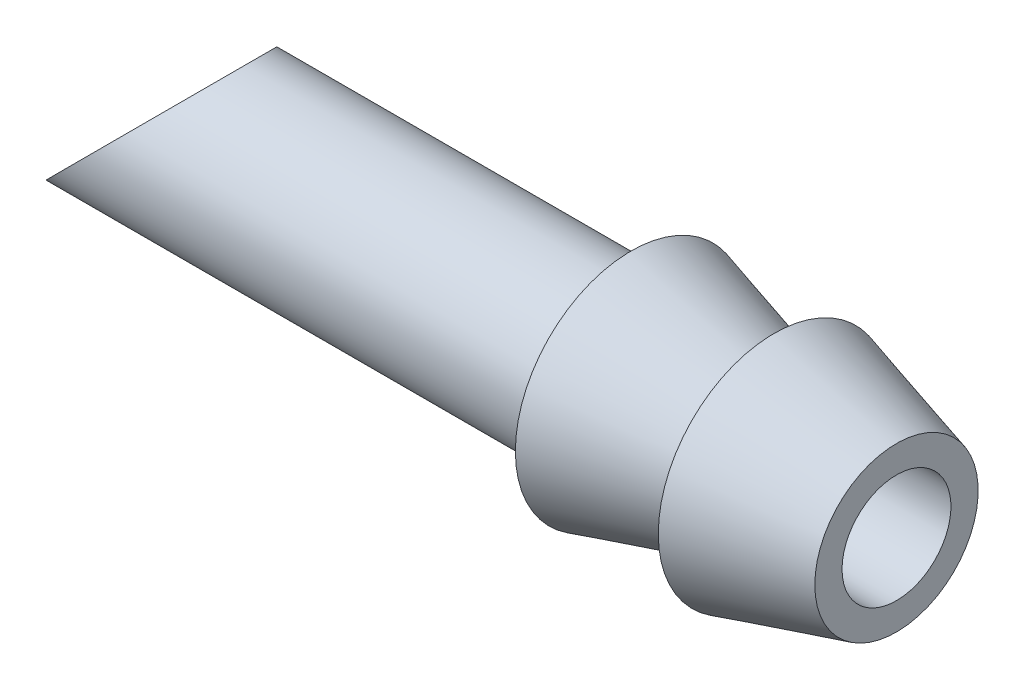
SolidWorks part; units mm, degrees
ref_plane "Front Plane" through (0, 0, 0) normal (0, 0, 1) x (1, 0, 0)
ref_plane "Top Plane" through (0, 0, 0) normal (0, 1, 0) x (1, 0, 0)
ref_plane "Right Plane" through (0, 0, 0) normal (1, 0, 0) x (0, 0, -1)
sketch "Sketch1" plane through (0, 0, 0) normal (0, 0, 1) x (1, 0, 0)
  line L0 (0, 0) -> (66.2675, 0) construction
  line L1 (0, 2) -> (0, 3)
  line L2 (0, 3) -> (20.25, 3)
  line L3 (30, 3) -> (30, 2)
  line L4 (30, 2) -> (0, 2)
  line L5 (20.25, 3) -> (20.25, 4.25)
  line L6 (20.25, 4.25) -> (24.75, 3)
  line L7 (25.5, 3) -> (25.5, 4.25)
  line L8 (25.5, 4.25) -> (30, 3)
  line L9 (24.75, 3) -> (25.5, 3)
  dimension "D1" = 30
  dimension "D2" = 1
  dimension "D3" = 3
  dimension "D4" = 4.5
  dimension "D5" = 4.5
  dimension "D6" = 1.25
  dimension "D7" = 1.25
  dimension "D8" = 0.75
revolve "Revolve1" add sketch "Sketch1" angle 360 about L0
sketch "Sketch2" plane through (0, 0, 0) normal (0, 0, 1) x (1, 0, 0)
  line L0 (0, -3) -> (6, 3)
  line L1 (20.25, 3) -> (0, 3) construction
  line L2 (0, 3) -> (0, -3) construction
  line L3 (0, -3) -> (0, 3)
  line L4 (0, 3) -> (6, 3)
  dimension "D1" = 45
extrude "Cut-Extrude1" cut sketch "Sketch2" against normal mid plane 10
